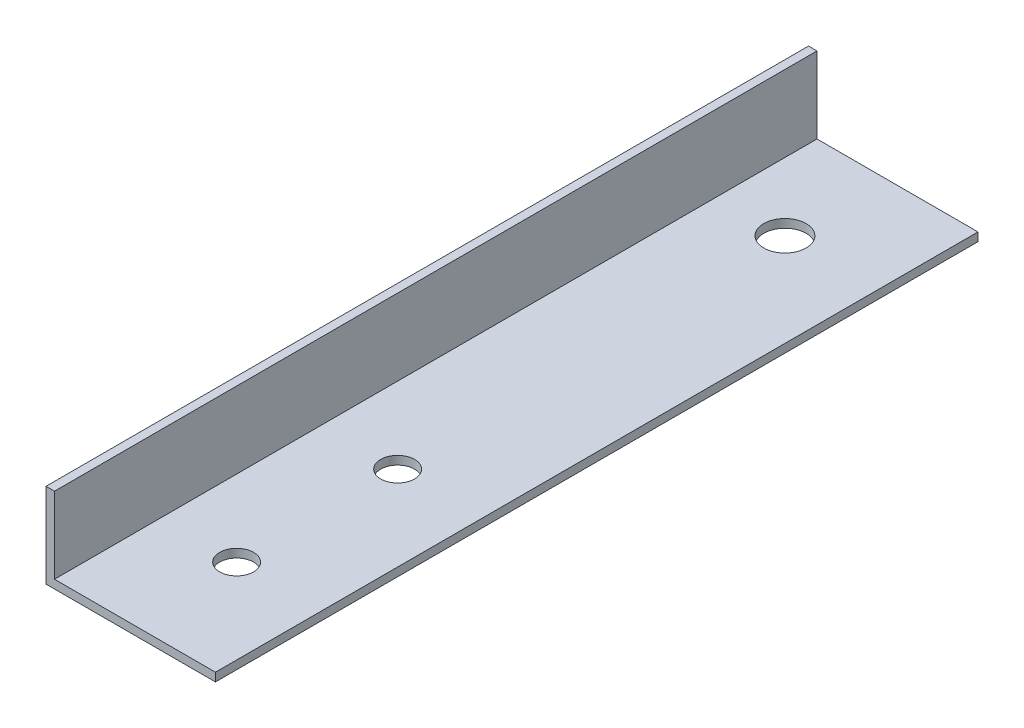
SolidWorks part; units mm, degrees
material "1060 Alloy"
ref_plane "Front Plane" through (0, 0, 0) normal (0, 0, 1) x (1, 0, 0)
ref_plane "Top Plane" through (0, 0, 0) normal (0, 1, 0) x (1, 0, 0)
ref_plane "Right Plane" through (0, 0, 0) normal (1, 0, 0) x (0, 0, -1)
sketch "Sketch1" plane through (0, 0, 0) normal (0, 0, 1) x (1, 0, 0)
  line L1 (-69.5798, 29.3277) -> (-67.5798, 29.3277)
  line L2 (-69.5798, 29.3277) -> (-69.5798, 11.3277)
  line L4 (-67.5798, 29.3277) -> (-67.5798, 11.3277)
  line L5 (-67.5798, 11.3277) -> (-29.5798, 11.3277)
  line L6 (-69.5798, 11.3277) -> (-69.5798, 9.3277)
  line L7 (-69.5798, 9.3277) -> (-29.5798, 9.3277)
  line L8 (-29.5798, 11.3277) -> (-29.5798, 9.3277)
  dimension "D1" = 20
  dimension "D2" = 40
  dimension "D3" = 2
  dimension "D4" = 2
extrude "Boss-Extrude1" add sketch "Sketch1" along normal blind 180
sketch "Sketch4" plane through (0, 9.3277, 0) normal (0, -1, 0) x (1, 0, 0)
  circle A0 centre (-49.5798, 155) radius 4
  circle A1 centre (-49.5798, 117) radius 4
  circle A2 centre (-51.5798, 23.5741) radius 5
  dimension "D2" = 10
  dimension "D1" = 0
extrude "Cut-Extrude5" cut sketch "Sketch4" against normal blind 10
